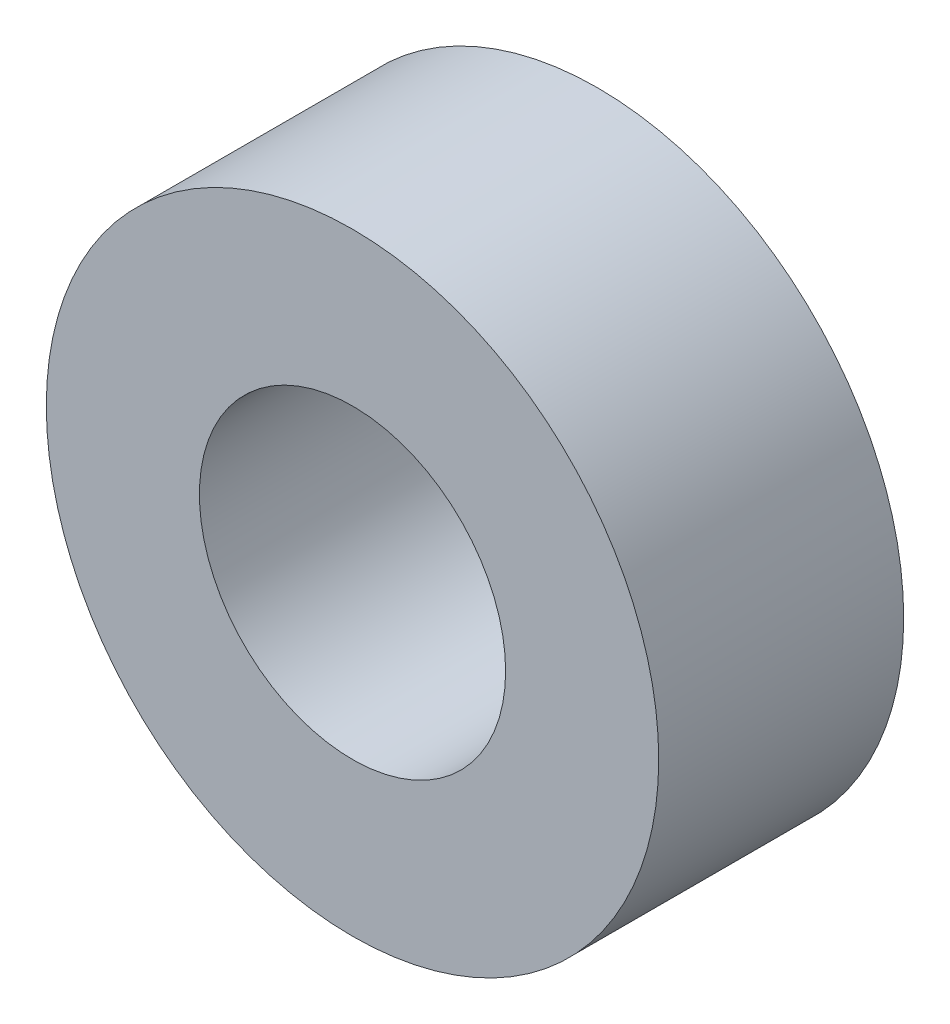
SolidWorks part; units mm, degrees
material "镀铬不锈钢"
ref_plane "前视基准面" through (0, 0, 0) normal (0, 0, 1) x (1, 0, 0)
ref_plane "上视基准面" through (0, 0, 0) normal (0, 1, 0) x (1, 0, 0)
ref_plane "右视基准面" through (0, 0, 0) normal (1, 0, 0) x (0, 0, -1)
sketch "草图1" plane through (0, 0, 0) normal (0, 0, 1) x (1, 0, 0)
  circle A0 centre (0, 0) radius 6
  dimension "D1" = 12
extrude "凸台-拉伸1" add sketch "草图1" along normal blind 1
sketch "草图2" plane through (0, 0, 1) normal (0, 0, 1) x (1, 0, 0)
  circle A0 centre (0, 0) radius 5
  dimension "D1" = 10
extrude "凸台-拉伸2" add sketch "草图2" along normal blind 3
sketch "草图3" plane through (0, 0, 4) normal (0, 0, 1) x (1, 0, 0)
  circle A0 centre (0, 0) radius 2.5
  dimension "D1" = 5
extrude "切除-拉伸1" cut sketch "草图3" against normal blind 7
sketch "草图4" plane through (0, 0, 1) normal (0, 0, 1) x (1, 0, 0)
  circle A0 centre (0, 0) radius 5
  circle A1 centre (0, 0) radius 6
  circle A2 centre (0, 0) radius 6
  dimension "D2" = 10
  dimension "D1" = 0
extrude "切除-拉伸2" cut sketch "草图4" against normal blind 10
